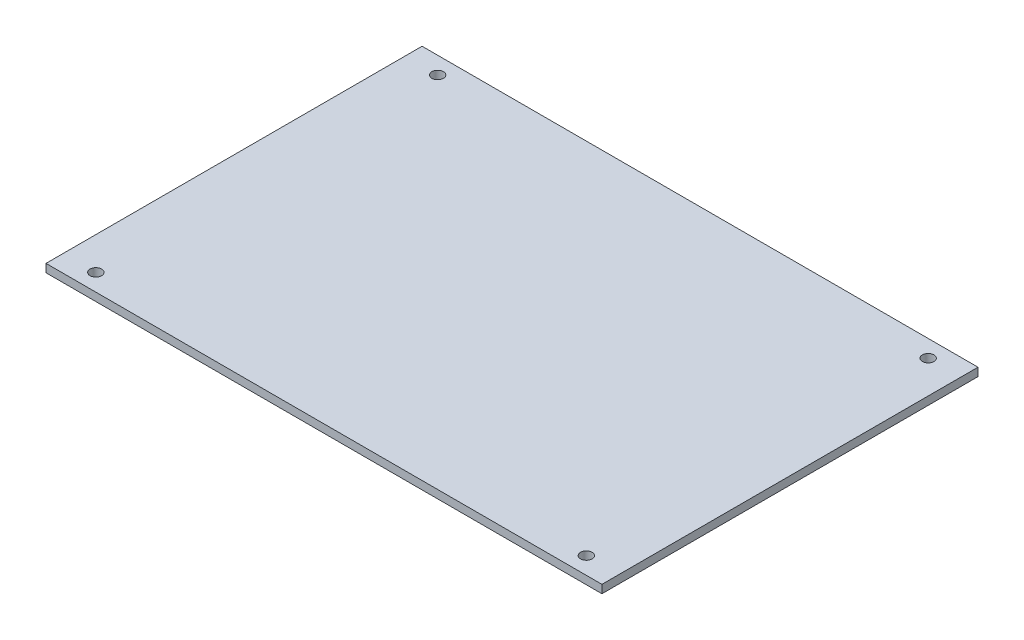
SolidWorks part; units mm, degrees
material "6061 Alloy"
ref_plane "Front Plane" through (0, 0, 0) normal (0, 0, 1) x (1, 0, 0)
ref_plane "Top Plane" through (0, 0, 0) normal (0, 1, 0) x (1, 0, 0)
ref_plane "Right Plane" through (0, 0, 0) normal (1, 0, 0) x (0, 0, -1)
sketch "Sketch1" plane through (0, 0, 0) normal (0, 1, 0) x (1, 0, 0)
  line L1 (-107.95, -73.025) -> (107.95, -73.025)
  line L2 (-107.95, -73.025) -> (-107.95, 73.025)
  line L3 (-107.95, 73.025) -> (107.95, 73.025)
  line L4 (107.95, -73.025) -> (107.95, 73.025)
  line L5 (-107.95, -73.025) -> (107.95, 73.025) construction
  line L6 (-107.95, 73.025) -> (107.95, -73.025) construction
  point P0 (0, 0)
  dimension "D1" = 146.05
  dimension "D2" = 215.9
extrude "Boss-Extrude1" add sketch "Sketch1" along normal blind 3.175
sketch "Sketch2" plane through (0, 3.175, 0) normal (0, 1, 0) x (1, 0, 0)
  line L2 (-95.25, 66.3813) -> (-95.25, -66.3813) construction
  line L3 (-95.25, -66.3813) -> (95.25, -66.3813) construction
  line L4 (95.25, -66.3813) -> (95.25, 66.3813) construction
  line L5 (95.25, 66.3813) -> (-95.25, 66.3813) construction
  line L6 (0, -1.7463) -> (0, 1.7463) construction
  line L7 (-1.7463, 0) -> (1.7463, 0) construction
  line L8 (107.95, 73.025) -> (-107.95, 73.025) construction
  point P0 (-95.25, 66.3813)
  point P5 (95.25, 66.3813)
  point P6 (95.25, -66.3813)
  point P7 (-95.25, -66.3813)
  point P14 (0, 66.3813)
  point P17 (95.25, 0)
  dimension "D1" = 190.5
  dimension "D2" = 6.6437
hole_wizard "#8 Clearance Hole2" positions "Sketch3" profile "Sketch5" hole size "#8" standard "ANSI Inch"
sketch "Sketch3" plane through (0, 3.175, 0) normal (0, 1, 0) x (1, 0, 0)
  point P0 (-95.25, 66.3813)
  point P3 (95.25, 66.3813)
  point P6 (95.25, -66.3813)
  point P9 (-95.25, -66.3813)
sketch "Sketch5" plane through (-95.25, 3.175, -66.3813) normal (1, 0, 0) x (0, 0, 1)
  line L0 (0, 0) -> (0, 14.0507)
  line L1 (0, 14.0507) -> (2.2479, 12.7)
  line L2 (2.2479, 12.7) -> (2.2479, 0)
  line L5 (2.2479, 0) -> (0, 0)
  line L10 (0, 14.0507) -> (-2.2479, 12.7) construction
  line L11 (0, -6.35) -> (0, 107.95) construction
  dimension "Hole Dia." = 4.4958
  dimension "Hole Depth" = 12.7
  dimension "Drill Angle" = 118
